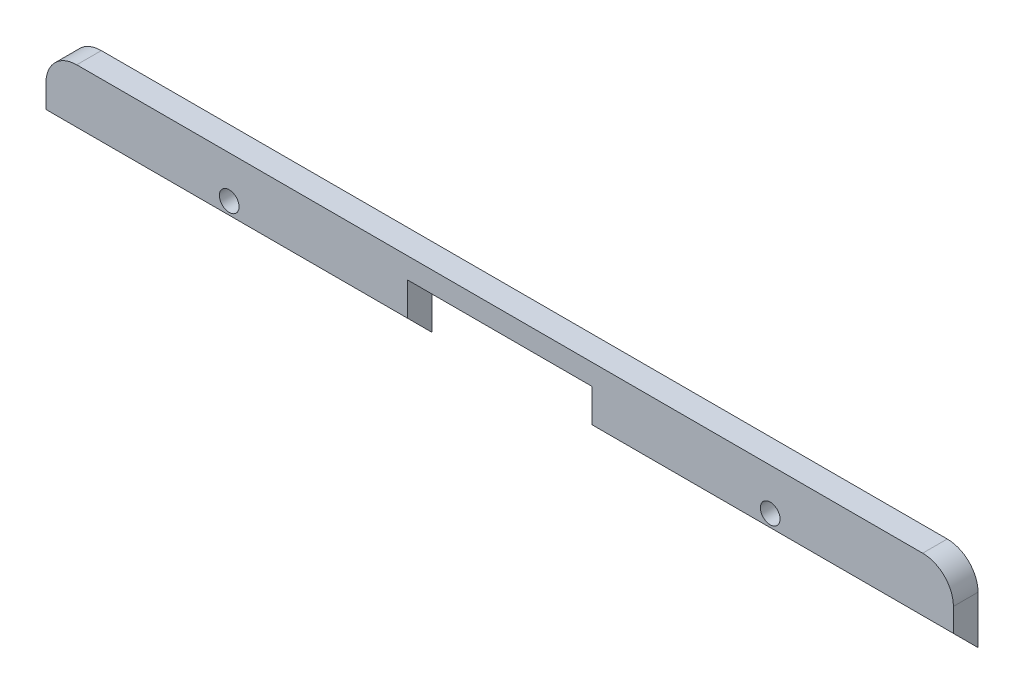
SolidWorks part; units mm, degrees
material "6061-T6 (SS)"
ref_plane "Front Plane" through (0, 0, 0) normal (0, 0, 1) x (1, 0, 0)
ref_plane "Top Plane" through (0, 0, 0) normal (0, 1, 0) x (1, 0, 0)
ref_plane "Right Plane" through (0, 0, 0) normal (1, 0, 0) x (0, 0, -1)
sketch "Sketch1" plane through (0, 0, 0) normal (1, 0, 0) x (0, 0, -1)
  line L0 (-3.0983, 0) -> (1.226, 0) construction
  line L1 (0, -3.2) -> (-2, -1.2)
  line L2 (0, -3.2) -> (0, 3.2)
  line L4 (-2, -1.2) -> (-2, 3.2)
  line L5 (-2, 3.2) -> (0, 3.2)
  dimension "D1" = 2
  dimension "D2" = 45
  dimension "D3" = 6.4
extrude "Boss-Extrude1" add sketch "Sketch1" along normal mid plane 73.8
sketch "Sketch4" plane through (0, 0, 0) normal (0, 0, 1) x (1, 0, 0)
  line L1 (7.5, 1.5) -> (-7.5, 1.5)
  line L2 (7.5, 1.5) -> (7.5, -3.2)
  line L3 (7.5, -3.2) -> (-7.5, -3.2)
  line L4 (-7.5, 1.5) -> (-7.5, -3.2)
  line L5 (0, 7.7759) -> (0, -8.8374) construction
  line L8 (-7.5, -3.2) -> (-7.5, 0.8) construction
  dimension "D1" = 4.7
hole_wizard "M2x0.4 Tapped Hole1" positions "Sketch2" profile "Sketch3" tap size "M2x0.4" standard "ANSI Metric" end condition through all
sketch "Sketch2" plane through (0, 0, 2) normal (0, 0, 1) x (1, 0, 0)
  circle A0 centre (-22, -0.2) radius 1.2
  circle A1 centre (-22, -0.2) radius 1.2 construction
  circle A2 centre (22, -0.2) radius 1.2
  circle A3 centre (22, -0.2) radius 1.2 construction
  point P0 (22, -0.2)
  point P2 (0, -0.2)
  point P5 (-22, -0.2)
sketch "Sketch3" plane through (22, -0.2, 2) normal (1, 0, 0) x (0, -1, 0)
  line L0 (0, 0) -> (0, 2)
  line L1 (0, 2) -> (0.8, 2)
  line L2 (0.8, 2) -> (0.8, 0)
  line L5 (0.8, 0) -> (0, 0)
  line L11 (0, -6.35) -> (0, 107.95) construction
  dimension "Thru Tap Drill Dia." = 1.6
  dimension "Thru Tap Drill Depth" = 2
cosmetic thread "Hole Thread1"
cosmetic thread "Hole Thread2"
cosmetic thread "Hole Thread3"
extrude "Cut-Extrude4" cut sketch "Sketch4" along normal through all
fillet "Fillet3" radius 2.5 2 edges at (-36.9, 3.2, 1) (36.9, 3.2, 1)
